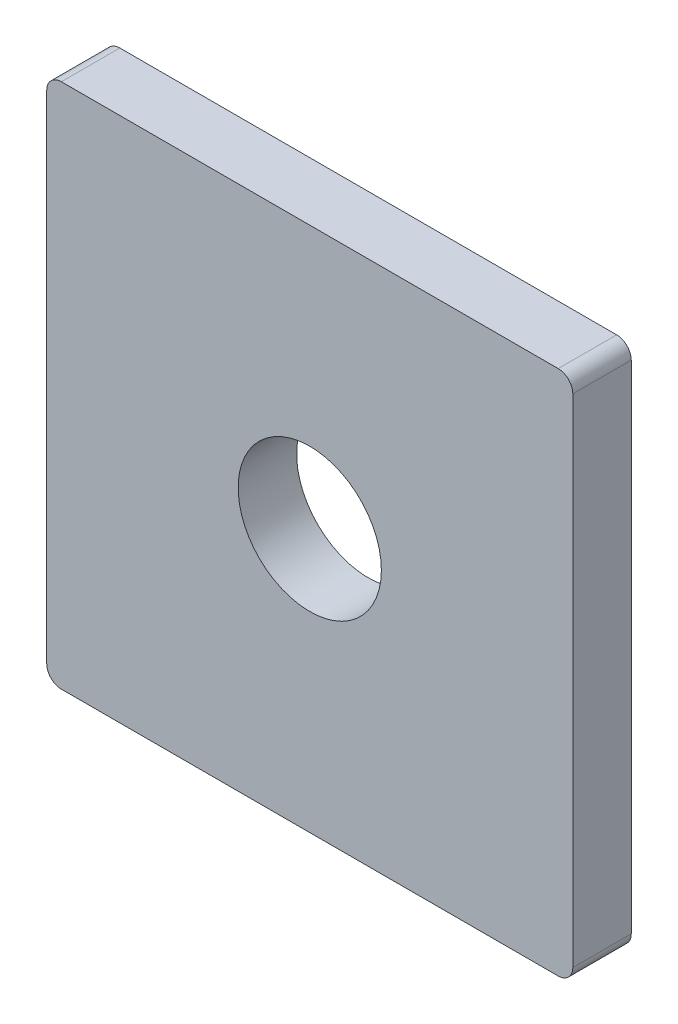
SolidWorks part; units mm, degrees
material "Brass"
ref_plane "Ebene vorne" through (0, 0, 0) normal (0, 0, 1) x (1, 0, 0)
ref_plane "Ebene oben" through (0, 0, 0) normal (0, 1, 0) x (1, 0, 0)
ref_plane "Ebene rechts" through (0, 0, 0) normal (1, 0, 0) x (0, 0, -1)
sketch "Sketch1" plane through (0, 0, 0) normal (0, 0, 1) x (1, 0, 0)
  line L1 (-9, 9) -> (9, 9)
  line L2 (-9, 9) -> (-9, -9)
  line L3 (-9, -9) -> (9, -9)
  line L4 (9, 9) -> (9, -9)
  line L5 (-9, 9) -> (9, -9) construction
  line L6 (-9, -9) -> (9, 9) construction
  circle A0 centre (0, 0) radius 2.45
  point P0 (0, 0)
  dimension "D2" = 4.9
  dimension "D1" = 18
extrude "Boss-Extrude1" add sketch "Sketch1" along normal blind 2
fillet "Fillet1" radius 0.5 4 edges at (-9, -9, 1) (-9, 9, 1) (9, -9, 1) (9, 9, 1)
